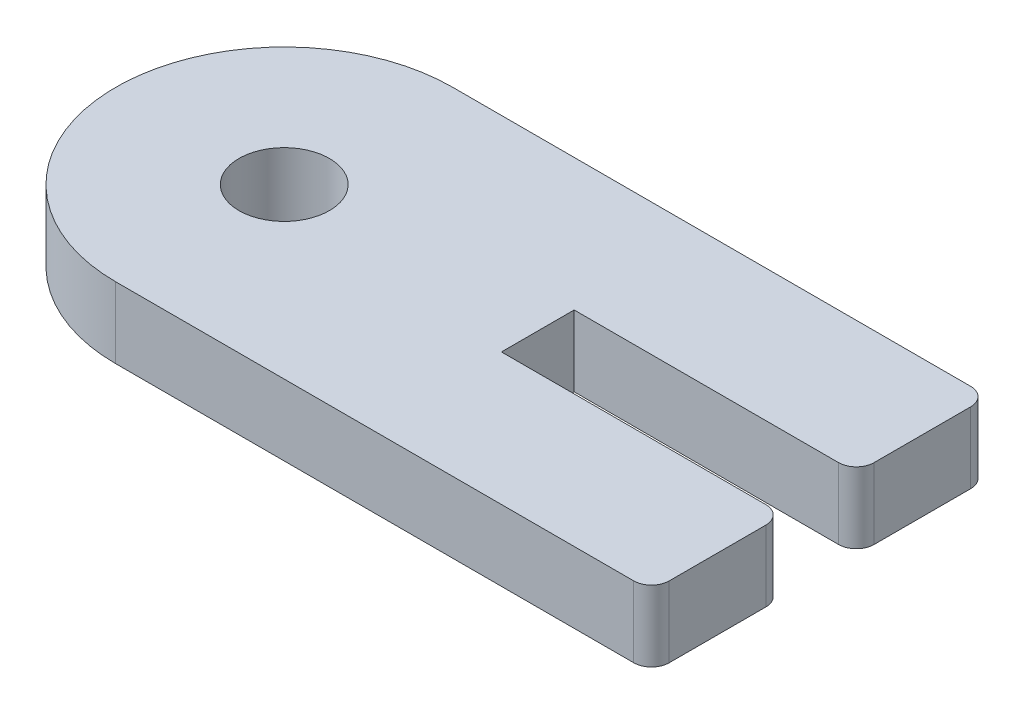
SolidWorks part; units mm, degrees
ref_plane "Front Plane" through (0, 0, 0) normal (0, 0, 1) x (1, 0, 0)
ref_plane "Top Plane" through (0, 0, 0) normal (0, 1, 0) x (1, 0, 0)
ref_plane "Right Plane" through (0, 0, 0) normal (1, 0, 0) x (0, 0, -1)
sketch "Sketch1" plane through (0, 0, 0) normal (0, 1, 0) x (1, 0, 0)
  line L0 (-12.15, 0) -> (12.15, 0) construction
  line L1 (-12.15, -9.5) -> (12.15, -9.5) construction
  line L2 (-12.15, -9.5) -> (-12.15, 9.5) construction
  line L3 (-12.15, 9.5) -> (12.15, 9.5) construction
  line L4 (12.15, -9.5) -> (12.15, 9.5) construction
  line L5 (-12.15, -9.5) -> (12.15, 9.5) construction
  line L6 (-12.15, 9.5) -> (12.15, -9.5) construction
  line L7 (28.06, -9.5) -> (28.06, 9.5) construction
  line L8 (7.85, 9.5) -> (7.85, -9.5) construction
  line L9 (27.06, 2.05) -> (12.15, 2.05)
  line L10 (12.15, 2.05) -> (12.15, -2.05)
  line L11 (27.06, -2.05) -> (12.15, -2.05)
  line L12 (-2.15, 9.5) -> (27.06, 9.5)
  line L13 (28.06, 8.5) -> (28.06, 3.05)
  line L14 (28.06, -3.05) -> (28.06, -8.5)
  line L15 (27.06, -9.5) -> (-2.15, -9.5)
  circle A0 centre (-2.15, 0) radius 2.55
  circle A1 centre (-2.15, 0) radius 9.5 construction
  arc A2 (-2.15, 9.5) -> (-2.15, -9.5) centre (-2.15, 0) ccw
  arc A3 (27.06, 9.5) -> (28.06, 8.5) centre (27.06, 8.5) cw
  arc A4 (28.06, -8.5) -> (27.06, -9.5) centre (27.06, -8.5) cw
  arc A5 (27.06, -2.05) -> (28.06, -3.05) centre (27.06, -3.05) cw
  arc A6 (27.06, 2.05) -> (28.06, 3.05) centre (27.06, 3.05) ccw
  point P0 (0, 0)
  point P30 (28.06, -2.05)
  point P33 (28.06, 2.05)
  dimension "D3" = 5.1
  dimension "D4" = 10
  dimension "D8" = 1
  dimension "D1" = 10
  dimension "D2" = 19
  dimension "D6" = 4.3
  dimension "D7" = 4.1
  dimension "D5" = 15.91
extrude "Boss-Extrude1" add sketch "Sketch1" along normal blind 4
